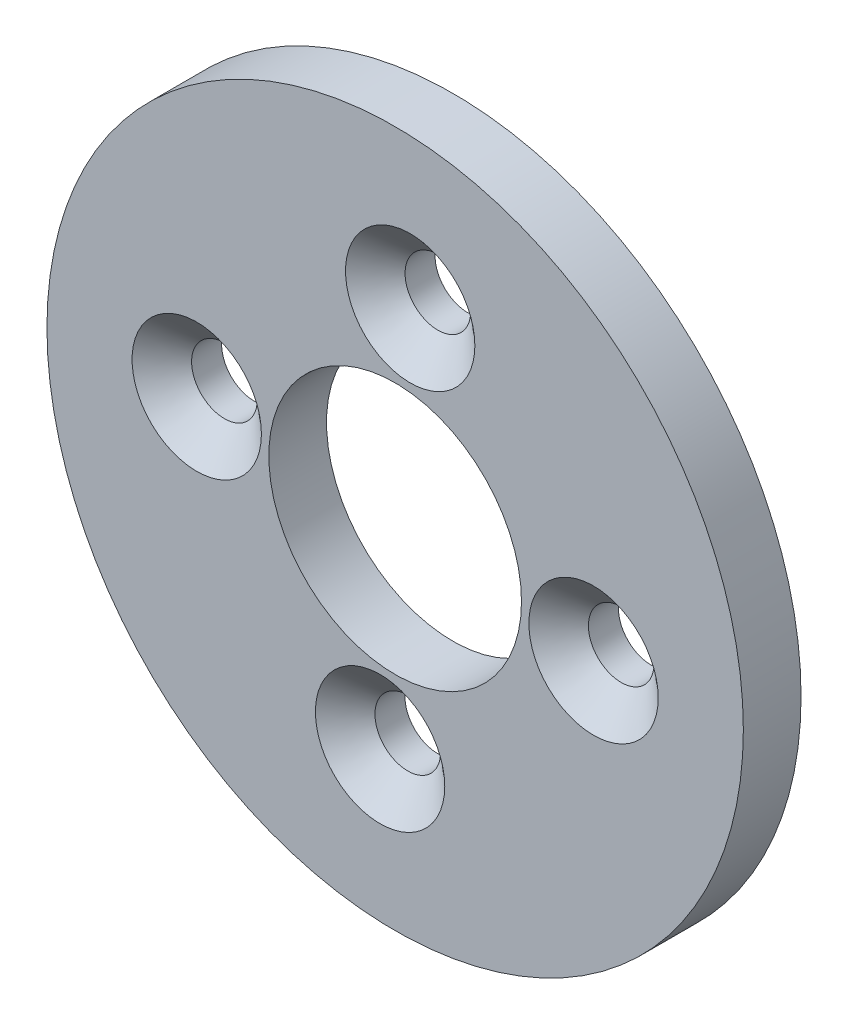
SolidWorks part; units mm, degrees
ref_plane "Front Plane" through (0, 0, 0) normal (0, 0, 1) x (1, 0, 0)
ref_plane "Top Plane" through (0, 0, 0) normal (0, 1, 0) x (1, 0, 0)
ref_plane "Right Plane" through (0, 0, 0) normal (1, 0, 0) x (0, 0, -1)
sketch "Sketch1" plane through (0, 0, 0) normal (0, 0, 1) x (1, 0, 0)
  circle A0 centre (0, 0) radius 17.5
  dimension "D1" = 35
extrude "Boss-Extrude1" add sketch "Sketch1" along normal blind 2.9
sketch "Sketch2" plane through (0, 0, 2.9) normal (0, 0, 1) x (1, 0, 0)
  circle A1 centre (-9.9713, 0.7566) radius 1.65
  circle A2 centre (-9.9713, 0.7566) radius 1.65
  circle A3 centre (-0.7566, -9.9713) radius 1.65
  circle A4 centre (-0.7566, -9.9713) radius 1.65
  circle A5 centre (9.9713, -0.7566) radius 1.65
  circle A6 centre (9.9713, -0.7566) radius 1.65
  circle A7 centre (0.7566, 9.9713) radius 1.65
  circle A8 centre (0.7566, 9.9713) radius 1.65
  dimension "D1" = 0
  dimension "D2" = 0
  dimension "D3" = 0
  dimension "D4" = 0
extrude "Cut-Extrude1" cut sketch "Sketch2" against normal through all
chamfer "Chamfer1" distance 1.6 angle 41 4 edges at (0.8934, -9.9713, 2.9) (-8.3213, 0.7566, 2.9) (2.4066, 9.9713, 2.9) (11.6213, -0.7566, 2.9)
sketch "Sketch3" plane through (0, 0, 2.9) normal (0, 0, 1) x (1, 0, 0)
  circle A1 centre (0, 0) radius 6.35
  circle A2 centre (0, 0) radius 6.35
  dimension "D1" = 0
extrude "Cut-Extrude2" cut sketch "Sketch3" against normal through all
equation "\"smallPulleyTeeth\"= 15"
equation "\"largePulleyTeeth\"= 30"
equation "\"eighthThick\"= 2.9mm"
equation "\"sixteenthThick\" = 1.7mm"
equation "\"quarterThick\"=5.6mm"
equation "\"OD\" = 150mm"
equation "\"puckAngle\" = 60.5deg"
equation "\"puckDiam\" = 76.5mm"
equation "\"axlePress\" = 5.8mm"
equation "\"press\" = 0.3mm"
equation "\"wheelClear\" = 0.3mm"
equation "\"10-32clear\" = 4.5mm"
equation "\"D1@Boss-Extrude1\"=\"eighthThick\""
equation "\"D1@Chamfer1\"=(6.5-\"6-32clear\")/2"
equation "\"6-32clear\" = 3.3mm"
equation "\"8-32clear\" = 4.0mm"
